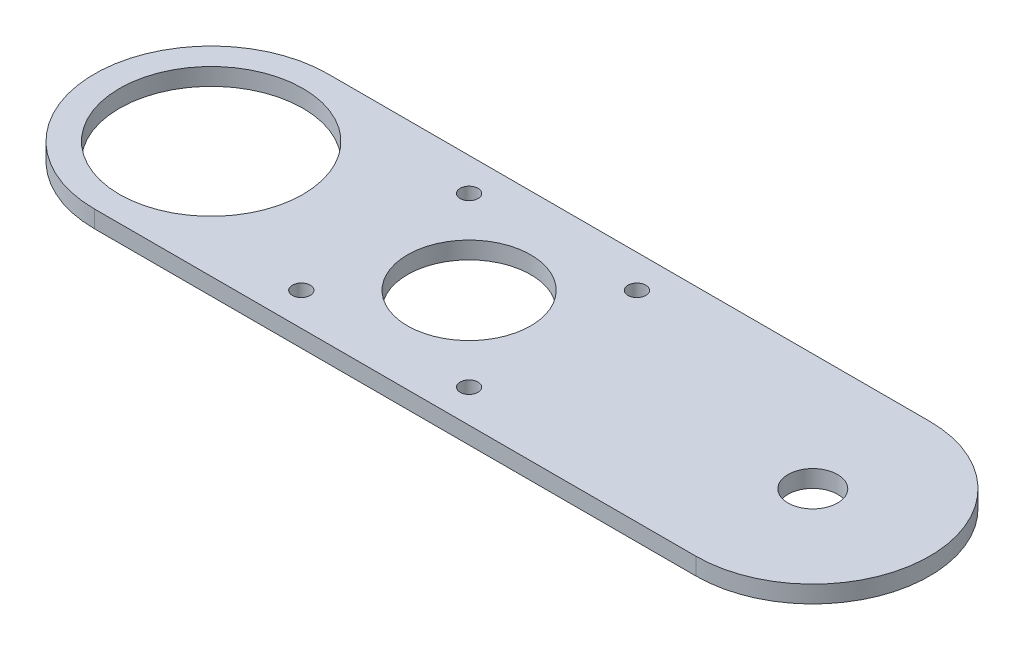
SolidWorks part; units mm, degrees
ref_plane "Front Plane" through (0, 0, 0) normal (0, 0, 1) x (1, 0, 0)
ref_plane "Top Plane" through (0, 0, 0) normal (0, 1, 0) x (1, 0, 0)
ref_plane "Right Plane" through (0, 0, 0) normal (1, 0, 0) x (0, 0, -1)
sketch "Sketch1" plane through (0, 0, 0) normal (0, 1, 0) x (1, 0, 0)
  line L0 (0, 0) -> (111.1504, 0) construction
  line L1 (0, 21.59) -> (111.1504, 21.59)
  line L2 (0, -21.59) -> (111.1504, -21.59)
  line L3 (55.5752, 21.59) -> (55.5752, -21.59) construction
  line L4 (0, 0) -> (111.1504, 0) construction
  line L5 (32.1504, -15.5) -> (63.1504, -15.5) construction
  line L6 (32.1504, -15.5) -> (32.1504, 15.5) construction
  line L7 (32.1504, 15.5) -> (63.1504, 15.5) construction
  line L8 (63.1504, -15.5) -> (63.1504, 15.5) construction
  line L9 (32.1504, -15.5) -> (63.1504, 15.5) construction
  line L10 (32.1504, 15.5) -> (63.1504, -15.5) construction
  line L11 (32.1504, 0) -> (63.1504, 0) construction
  line L12 (47.6504, -15.5) -> (47.6504, 15.5) construction
  arc A0 (0, 21.59) -> (0, -21.59) centre (0, 0) ccw
  arc A1 (111.1504, -21.59) -> (111.1504, 21.59) centre (111.1504, 0) ccw
  circle A2 centre (0, 0) radius 16.9545
  circle A3 centre (111.1504, 0) radius 4.572
  circle A4 centre (47.6504, 0) radius 11.381
  circle A5 centre (32.1504, -15.5) radius 1.651
  circle A6 centre (32.1504, 15.5) radius 1.651
  circle A7 centre (63.1504, 15.5) radius 1.651
  circle A8 centre (63.1504, -15.5) radius 1.651
  point P3 (55.5752, 0)
  dimension "D2" = 21.59
  dimension "D3" = 33.909
  dimension "D4" = 9.144
  dimension "D5" = 22.762
  dimension "D7" = 3.302
  dimension "D10" = 3.302
  dimension "D1" = 111.1504
  dimension "D6" = 63.5
  dimension "D8" = 31
  dimension "D9" = 31
extrude "Boss-Extrude1" add sketch "Sketch1" along normal blind 3.175
